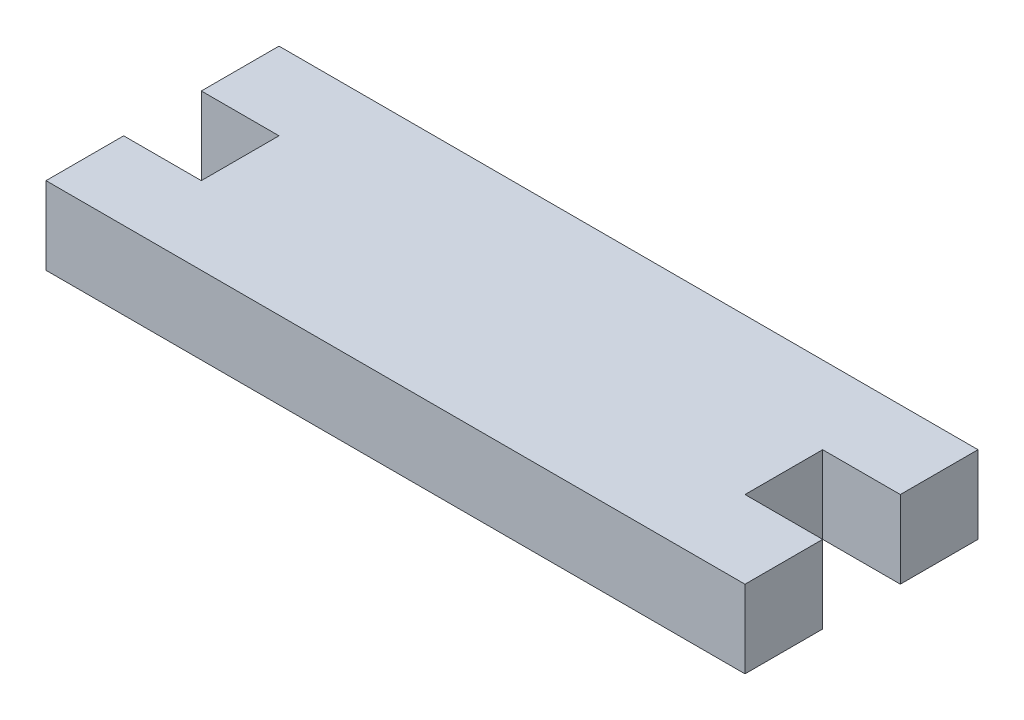
SolidWorks part; units mm, degrees
ref_plane "Front Plane" through (0, 0, 0) normal (0, 0, 1) x (1, 0, 0)
ref_plane "Top Plane" through (0, 0, 0) normal (0, 1, 0) x (1, 0, 0)
ref_plane "Right Plane" through (0, 0, 0) normal (1, 0, 0) x (0, 0, -1)
sketch "Sketch1" plane through (0, 0, 0) normal (0, 1, 0) x (1, 0, 0)
  line L0 (-28.575, -9.525) -> (-28.575, -3.175)
  line L1 (-28.575, -9.525) -> (28.575, -9.525)
  line L2 (-28.575, 3.175) -> (-28.575, 9.525)
  line L3 (-28.575, 9.525) -> (28.575, 9.525)
  line L4 (28.575, -3.175) -> (28.575, -9.525)
  line L5 (-28.575, -9.525) -> (28.575, 9.525) construction
  line L6 (-28.575, 9.525) -> (28.575, -9.525) construction
  line L7 (-28.575, -3.175) -> (-22.225, -3.175)
  line L8 (-22.225, -3.175) -> (-22.225, 3.175)
  line L9 (-22.225, 3.175) -> (-28.575, 3.175)
  line L10 (0, 9.525) -> (0, -9.525) construction
  line L11 (22.225, 3.175) -> (28.575, 3.175)
  line L12 (22.225, -3.175) -> (22.225, 3.175)
  line L13 (28.575, -3.175) -> (22.225, -3.175)
  line L14 (28.575, 9.525) -> (28.575, 3.175)
  point P0 (0, 0)
  point P12 (28.575, -3.175)
  point P13 (28.575, 3.175)
  dimension "D1" = 6.35
  dimension "D2" = 6.35
  dimension "D3" = 6.35
  dimension "D4" = 6.35
extrude "Boss-Extrude1" add sketch "Sketch1" along normal blind 6.35
